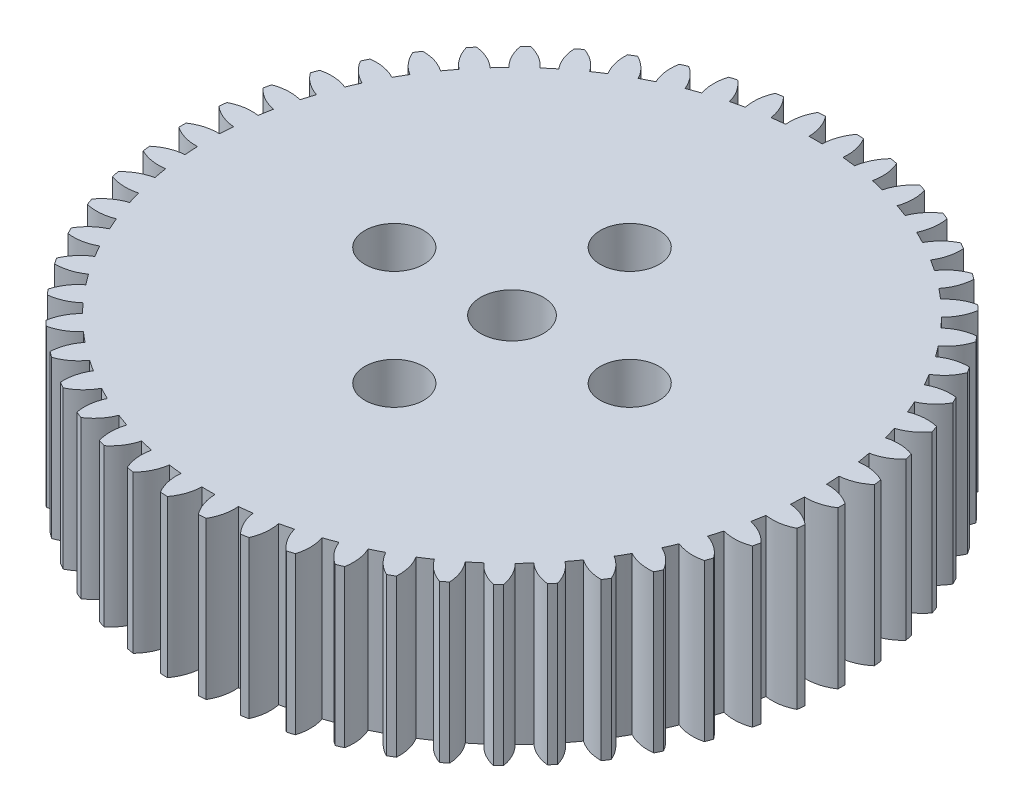
SolidWorks part; units mm, degrees
ref_plane "Ebene vorne" through (0, 0, 0) normal (0, 0, 1) x (1, 0, 0)
ref_plane "Ebene oben" through (0, 0, 0) normal (0, 1, 0) x (1, 0, 0)
ref_plane "Ebene rechts" through (0, 0, 0) normal (1, 0, 0) x (0, 0, -1)
sketch "Skizze1" plane through (0, 0, 0) normal (0, 1, 0) x (1, 0, 0)
  circle A0 centre (0, 0) radius 16.8
  dimension "D1" = 33.6
extrude "Aufsatz-Linear austragen1" add sketch "Skizze1" along normal blind 8
sketch "Skizze2" plane through (0, 8, 0) normal (0, 1, 0) x (1, 0, 0)
  line L0 (0, 0) -> (0, 16.8) construction
  line L1 (0, 0) -> (-0.3367, 15.4763) construction
  line L2 (0, 0) -> (0.9768, 16.7716) construction
  line L3 (-0.4712, 16.1931) -> (0.4712, 16.1931) construction
  line L4 (0.4712, 16.1931) -> (1.4119, 16.1384) construction
  line L5 (0, 14.8986) -> (-0.6869, 16.786) construction
  circle A0 centre (0, 0) radius 16.8
  circle A1 centre (0, 0) radius 16.2 construction
  circle A2 centre (0, 0) radius 15.48
  arc A3 (-0.792, 16.7813) -> (-0.3367, 15.4763) centre (-2.5744, 15.4277) cw
  arc A4 (0.792, 16.7813) -> (0.3367, 15.4763) centre (2.5744, 15.4277) ccw
  dimension "D3" = 33.6
  dimension "D4" = 32.4
  dimension "D5" = 30.96
  dimension "D1" = 3.333
  dimension "D2" = 20
extrude "Schnitt-Linear austragen1" cut sketch "Skizze2" against normal blind 8 contours A4 A0 A3 A2
pattern_circular "Kreismuster1" count 54 over 360 about axis through (0, 0, 0) along (0, 1, 0) of "Schnitt-Linear austragen1"
sketch "Skizze3" plane through (0, 0, 0) normal (0, -1, 0) x (1, 0, 0)
  circle A0 centre (0, 0) radius 1.6
  dimension "D1" = 3.2
extrude "Schnitt-Linear austragen2" cut sketch "Skizze3" against normal up to surface (8 mm away) up to face at (0, 8, 0)
sketch "Skizze4" plane through (0, 0, 0) normal (0, -1, 0) x (1, 0, 0)
  line L0 (0, 0) -> (0, 6) construction
  circle A0 centre (0, 6) radius 1.5
  circle A1 centre (6, 0) radius 1.5
  circle A2 centre (0, -6) radius 1.5
  circle A3 centre (-6, 0) radius 1.5
  point P13 (0, 0)
  dimension "D1" = 3
  dimension "D2" = 6
  dimension "D3" = 4
extrude "Schnitt-Linear austragen3" cut sketch "Skizze4" against normal through all
equation "\"Tooth\"= 54"
equation "\"module\"= 0.6"
equation "\"D1@Skizze1\"=\"module\"*(\"Tooth\"+2)"
